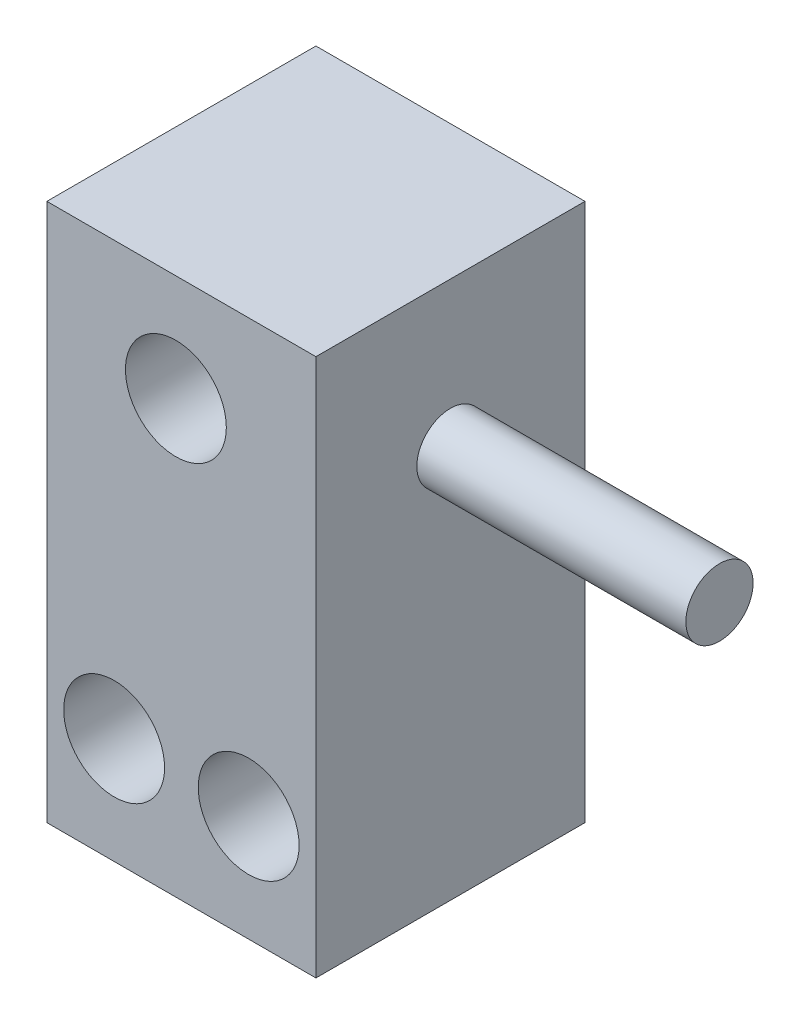
SolidWorks part; units mm, degrees
ref_plane "Front Plane" through (0, 0, 0) normal (0, 0, 1) x (1, 0, 0)
ref_plane "Top Plane" through (0, 0, 0) normal (0, 1, 0) x (1, 0, 0)
ref_plane "Right Plane" through (0, 0, 0) normal (1, 0, 0) x (0, 0, -1)
sketch "Sketch7" plane through (0, 0, 0) normal (0, 0, 1) x (1, 0, 0)
  line L1 (0, 0) -> (20, 0)
  line L2 (0, 0) -> (0, 40)
  line L3 (0, 40) -> (20, 40)
  line L4 (20, 0) -> (20, 40)
  circle A0 centre (15, 7.9067) radius 3.75
  circle A1 centre (5, 7.9067) radius 3.75
  circle A2 centre (9.59, 32.1) radius 3.75
  point P7 (10, 40)
  dimension "D3" = 5
  dimension "D4" = 5
  dimension "D5" = 7.5
  dimension "D6" = 7.9
  dimension "D7" = 7.5
  dimension "D8" = 7.9067
  dimension "D1" = 20
  dimension "D2" = 40
extrude "Boss-Extrude4" add sketch "Sketch7" along normal blind 20
sketch "Sketch8" plane through (20, 0, 0) normal (1, 0, 0) x (0, 0, -1)
  line L0 (-10, 0) -> (-10, 40) construction
  line L1 (-20, 0) -> (0, 0) construction
  line L2 (-20, 40) -> (0, 40) construction
  circle A0 centre (-10, 29.1763) radius 2.5
  point P8 (-10, 29.1763)
  dimension "D1" = 5
extrude "Boss-Extrude5" add sketch "Sketch8" along normal blind 20
